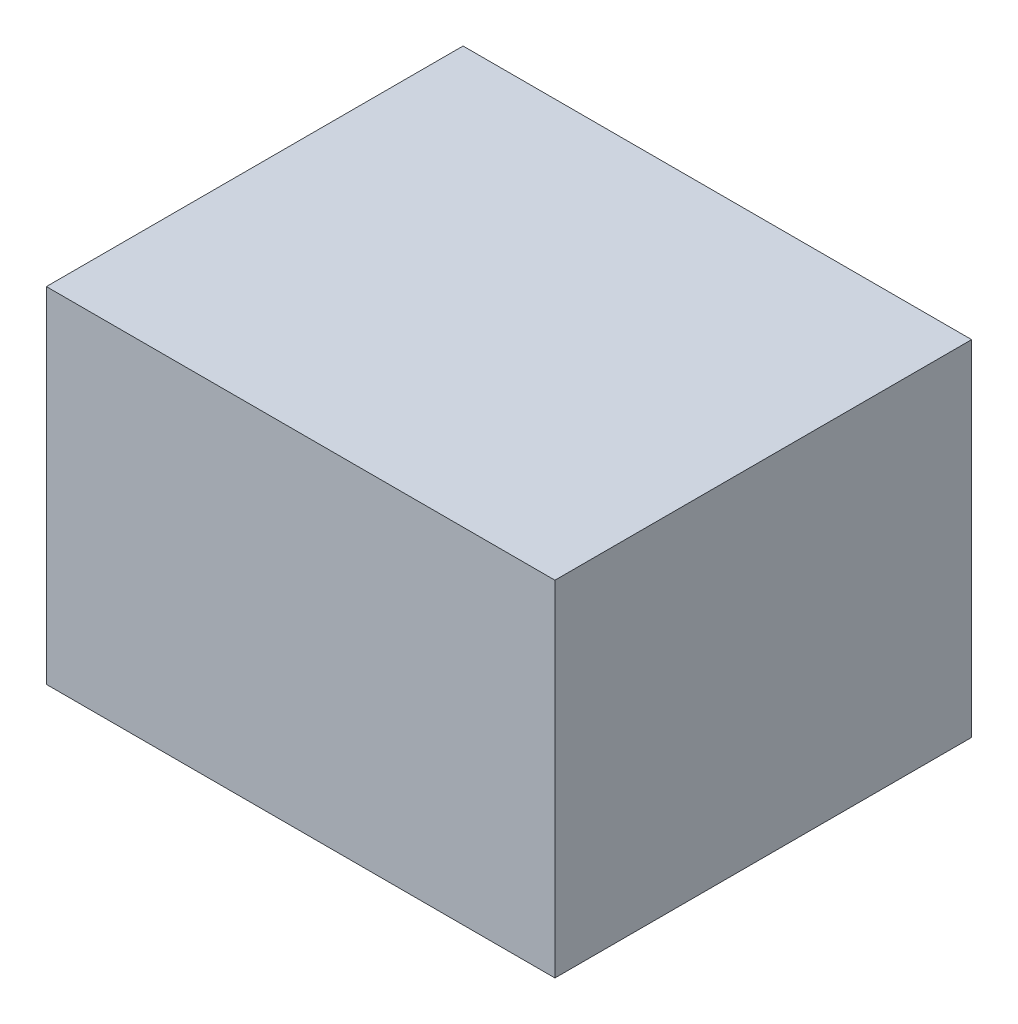
SolidWorks part; units mm, degrees
ref_plane "Alzado" through (0, 0, 0) normal (0, 0, 1) x (1, 0, 0)
ref_plane "Planta" through (0, 0, 0) normal (0, 1, 0) x (1, 0, 0)
ref_plane "Vista lateral" through (0, 0, 0) normal (1, 0, 0) x (0, 0, -1)
sketch "Croquis1" plane through (0, 0, 0) normal (0, 1, 0) x (1, 0, 0)
  line L1 (-7.75, -6.35) -> (7.75, -6.35)
  line L2 (-7.75, -6.35) -> (-7.75, 6.35)
  line L3 (-7.75, 6.35) -> (7.75, 6.35)
  line L4 (7.75, -6.35) -> (7.75, 6.35)
  line L5 (-7.75, -6.35) -> (7.75, 6.35) construction
  line L6 (-7.75, 6.35) -> (7.75, -6.35) construction
  point P0 (0, 0)
  dimension "D1" = 15.5
  dimension "D2" = 12.7
extrude "Saliente-Extruir1" add sketch "Croquis1" along normal mid plane 10.5
